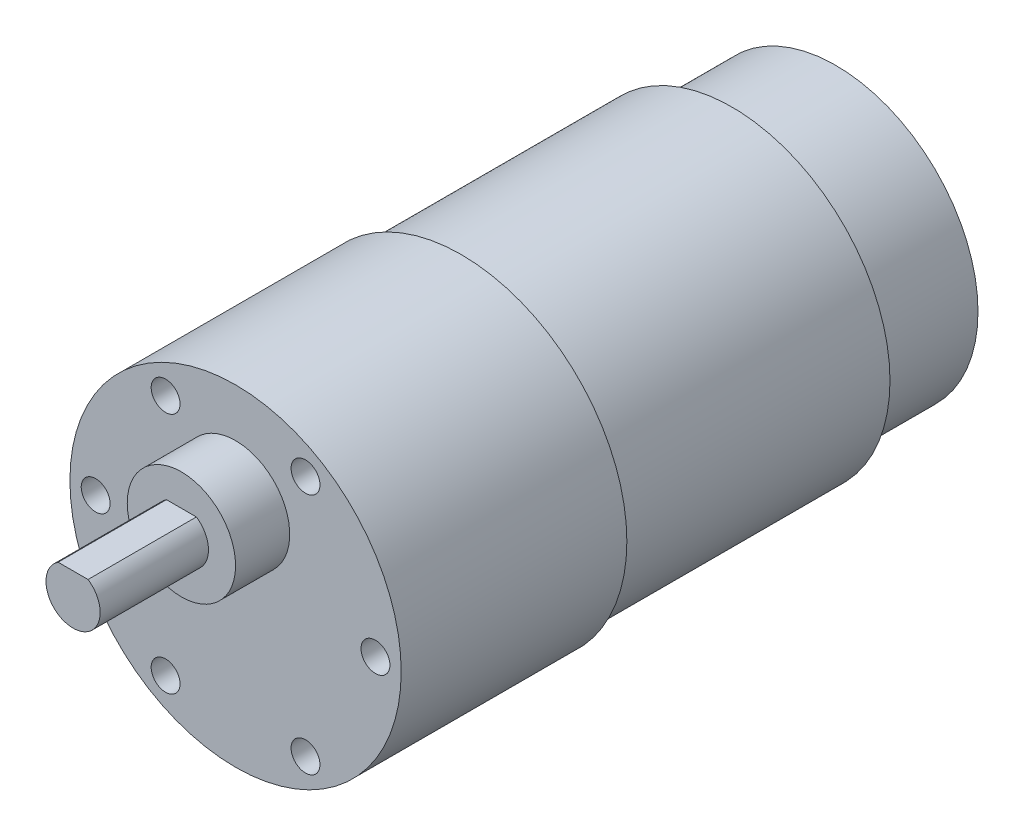
SolidWorks part; units mm, degrees
ref_plane "Front Plane" through (0, 0, 0) normal (0, 0, 1) x (1, 0, 0)
ref_plane "Top Plane" through (0, 0, 0) normal (0, 1, 0) x (1, 0, 0)
ref_plane "Right Plane" through (0, 0, 0) normal (1, 0, 0) x (0, 0, -1)
sketch "Sketch1" plane through (0, 0, 0) normal (1, 0, 0) x (0, 0, -1)
  line L0 (-25, -17.5) -> (41.5, -17.5) construction
  line L1 (0, 0) -> (30, 0)
  line L2 (0, 0) -> (0, -35)
  line L3 (0, -35) -> (30, -35)
  line L4 (30, 0) -> (30, -35)
  line L5 (0, -35.85) -> (-25, -35.85)
  line L6 (0, -35.85) -> (0, 0.85)
  line L7 (0, 0.85) -> (-25, 0.85)
  line L8 (-25, -35.85) -> (-25, 0.85)
  line L21 (30, -33.25) -> (41.5, -33.25)
  line L22 (30, -33.25) -> (30, -1.75)
  line L23 (30, -1.75) -> (41.5, -1.75)
  line L24 (41.5, -33.25) -> (41.5, -1.75)
  point P9 (0, -17.5)
  point P10 (0, -17.5)
  point P27 (30, -17.5)
  point P28 (30, -17.5)
  dimension "D1" = 30
  dimension "D2" = 35
  dimension "D3" = 36.7
  dimension "D4" = 25
  dimension "D9" = 11.5
  dimension "D10" = 31.5
revolve "Revolve1" add sketch "Sketch1" angle 360 about L0
sketch "Sketch2" plane through (0, 0, 25) normal (0, 0, 1) x (1, 0, 0)
  line L0 (18.35, -17.5) -> (-18.35, -17.5) construction
  line L1 (0, -17.5) -> (0, -10.5) construction
  circle A0 centre (0, -17.5) radius 18.35 construction
  circle A1 centre (0, -10.5) radius 6
  dimension "D2" = 12
  dimension "D1" = 7
extrude "Boss-Extrude1" add sketch "Sketch2" along normal blind 6
sketch "Sketch3" plane through (0, 0, 31) normal (0, 0, 1) x (1, 0, 0)
  circle A0 centre (0, -10.5) radius 3
  dimension "D1" = 6
extrude "Boss-Extrude2" add sketch "Sketch3" along normal blind 12
sketch "Sketch4" plane through (0, 0, 25) normal (0, 0, 1) x (1, 0, 0)
  line L0 (18.35, -17.5) -> (-18.35, -17.5) construction
  line L1 (0, -17.5) -> (0, 0) construction
  circle A0 centre (0, -17.5) radius 18.35 construction
  circle A1 centre (-15.5, -17.5) radius 1.6
  circle A2 centre (15.5, -17.5) radius 1.6
  circle A3 centre (0, -17.5) radius 15.5
  circle A4 centre (-7.75, -4.0766) radius 1.6
  circle A5 centre (7.75, -4.0766) radius 1.6
  circle A6 centre (7.75, -30.9234) radius 1.6
  circle A7 centre (-7.75, -30.9234) radius 1.6
  dimension "D1" = 3.2
  dimension "D3" = 15.5
extrude "Cut-Extrude1" cut sketch "Sketch4" against normal blind 6 contours A3 A4 | A3 A4 | A5 A3 | A5 A3 | A3 A2 | A2 A3 | A3 A6 | A3 A6 | A7 A3 | A7 A3 | A3 A1 | A1 A3
sketch "Sketch5" plane through (0, 0, 43) normal (0, 0, 1) x (1, 0, 0)
  line L0 (0, -13.5) -> (0, -8) construction
  line L1 (-1.6583, -8) -> (1.6583, -8)
  circle A0 centre (0, -10.5) radius 3 construction
  circle A1 centre (0, -10.5) radius 3 construction
  arc A2 (-1.6583, -8) -> (1.6583, -8) centre (0, -10.5) cw
  point P10 (0, -8)
  dimension "D1" = 5.5
extrude "Cut-Extrude2" cut sketch "Sketch5" against normal up to surface (12 mm away) and the other way through all up to face at (3, -10.5, 31)
